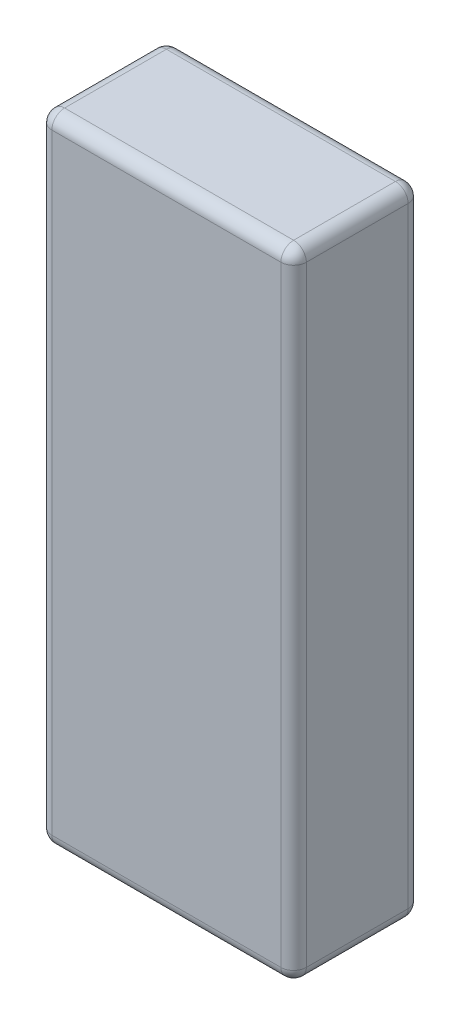
SolidWorks part; units mm, degrees
ref_plane "前视基准面" through (0, 0, 0) normal (0, 0, 1) x (1, 0, 0)
ref_plane "上视基准面" through (0, 0, 0) normal (0, 1, 0) x (1, 0, 0)
ref_plane "右视基准面" through (0, 0, 0) normal (1, 0, 0) x (0, 0, -1)
sketch "草图1" plane through (0, 0, 0) normal (0, 0, 1) x (1, 0, 0)
  line L1 (-10, -25) -> (10, -25)
  line L2 (-10, -25) -> (-10, 25)
  line L3 (-10, 25) -> (10, 25)
  line L4 (10, -25) -> (10, 25)
  line L5 (-10, -25) -> (10, 25) construction
  line L6 (-10, 25) -> (10, -25) construction
  point P0 (0, 0)
  dimension "D1" = 20
  dimension "D2" = 50
extrude "凸台-拉伸1" add sketch "草图1" along normal blind 10
fillet "圆角1" radius 1 12 edges at (-10, -25, 5) (0, -25, 10) (10, -25, 5) (0, -25, 0) (10, 0, 0) (10, 0, 10) (-10, 0, 10) (-10, 0, 0) (-10, 25, 5) (10, 25, 5) (0, 25, 10) (0, 25, 0)
